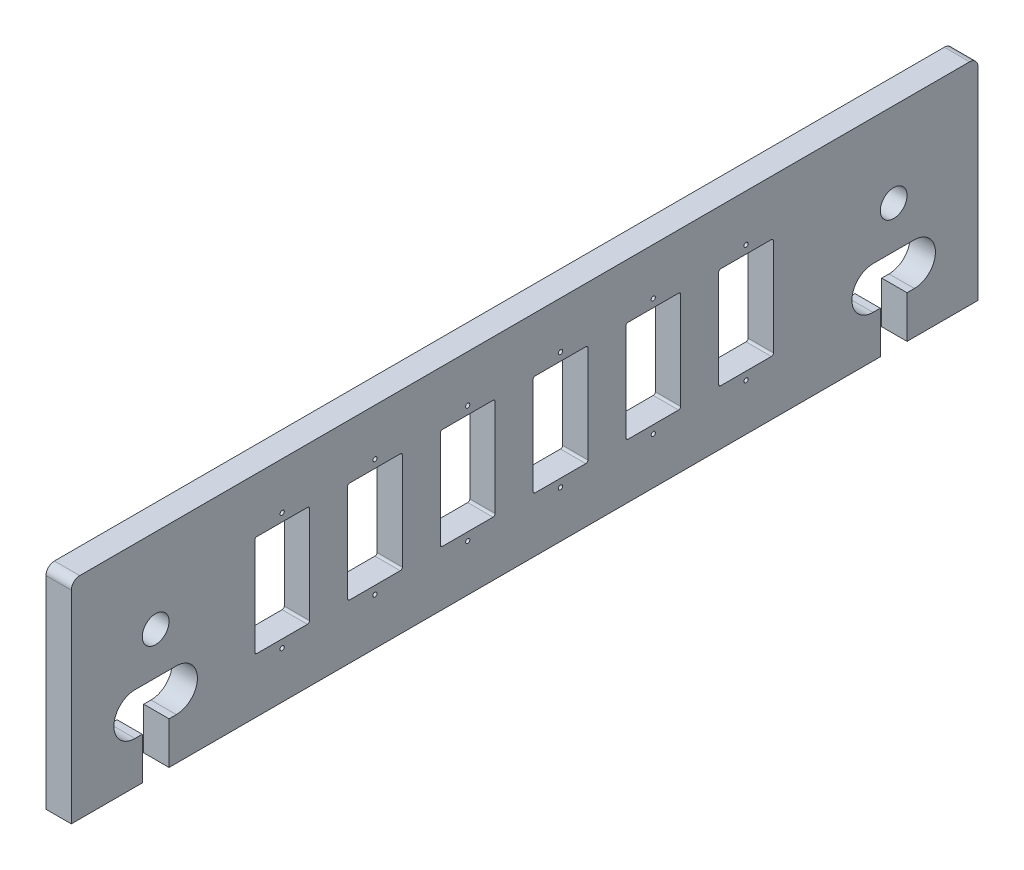
SolidWorks part; units mm, degrees
material "Delrin 2700 NC010, Low Viscosity Acetal Copolymer (SS)"
ref_plane "Front" through (0, 0, 0) normal (0, 0, 1) x (1, 0, 0)
ref_plane "Top" through (0, 0, 0) normal (0, 1, 0) x (1, 0, 0)
ref_plane "Right" through (0, 0, 0) normal (1, 0, 0) x (0, 0, -1)
sketch "Sketch1" plane through (0, 0, 0) normal (1, 0, 0) x (0, 0, -1)
  line L0 (-3.175, 0) -> (-20, 0)
  line L1 (-20, 0) -> (-20, 48)
  line L2 (-18, 50) -> (193, 50)
  line L3 (195, 48) -> (195, 0)
  line L4 (195, 0) -> (178.175, 0)
  line L5 (0, 0) -> (0, 20) construction
  line L6 (87.5, 0) -> (87.5, 50) construction
  line L7 (178.175, 0) -> (178.175, 10)
  line L8 (178.175, 10) -> (179.9, 10)
  line L9 (179.9, 20) -> (170.1, 20)
  line L10 (-3.175, 0) -> (-3.175, 10)
  line L11 (-3.175, 10) -> (-4.9, 10)
  line L12 (-4.9, 20) -> (4.9, 20)
  line L13 (3.175, 10) -> (4.9, 10)
  line L14 (3.175, 0) -> (3.175, 10)
  line L15 (171.825, 10) -> (170.1, 10)
  line L16 (171.825, 0) -> (171.825, 10)
  line L17 (171.825, 0) -> (3.175, 0)
  circle A0 centre (175, 30) radius 3.175
  arc A1 (179.9, 10) -> (179.9, 20) centre (179.9, 15) ccw
  arc A2 (170.1, 10) -> (170.1, 20) centre (170.1, 15) cw
  arc A4 (-4.9, 10) -> (-4.9, 20) centre (-4.9, 15) cw
  arc A5 (4.9, 10) -> (4.9, 20) centre (4.9, 15) ccw
  arc A6 (195, 48) -> (193, 50) centre (193, 48) ccw
  arc A7 (-18, 50) -> (-20, 48) centre (-18, 48) ccw
  circle A8 centre (0, 30) radius 3.175
  dimension "D2" = 50
  dimension "D5" = 5
  dimension "D15" = 2
  dimension "D16" = 6.35
  dimension "D3" = 6.35
  dimension "D4" = 9.8
  dimension "D6" = 10
  dimension "D7" = 30
  dimension "D8" = 175
  dimension "D14" = 215
extrude "Boss-Extrude1" add sketch "Sketch1" along normal blind 6
sketch "Sketch2" plane through (6, 0, 0) normal (1, 0, 0) x (0, 0, -1)
  line L0 (30, 0) -> (30, 50) construction
  line L1 (3.175, 0) -> (171.825, 0) construction
  line L2 (193, 50) -> (-18, 50) construction
  line L3 (24, 13) -> (36, 13)
  line L4 (36.5, 13.5) -> (36.5, 36.5)
  line L5 (36, 37) -> (24, 37)
  line L6 (23.5, 13.5) -> (23.5, 36.5)
  line L7 (23.5, 25) -> (36.5, 25) construction
  line L8 (-20, 48) -> (-20, 0) construction
  arc A0 (36, 13) -> (36.5, 13.5) centre (36, 13.5) ccw
  arc A1 (36.5, 36.5) -> (36, 37) centre (36, 36.5) ccw
  arc A2 (23.5, 36.5) -> (24, 37) centre (24, 36.5) cw
  arc A3 (24, 13) -> (23.5, 13.5) centre (24, 13.5) cw
  circle A4 centre (30, 38.9) radius 0.5
  circle A5 centre (30, 11.1) radius 0.5
  point P15 (30, 13)
  point P20 (30, 37)
  dimension "D1" = 0.5
  dimension "D5" = 1
  dimension "D2" = 24
  dimension "D3" = 13
  dimension "D4" = 50
  dimension "D6" = 27.8
extrude "servo mount" cut sketch "Sketch2" against normal up to next
pattern_linear "LPattern1" count 6 spacing 22 along (0, 0, -1) of "servo mount"
